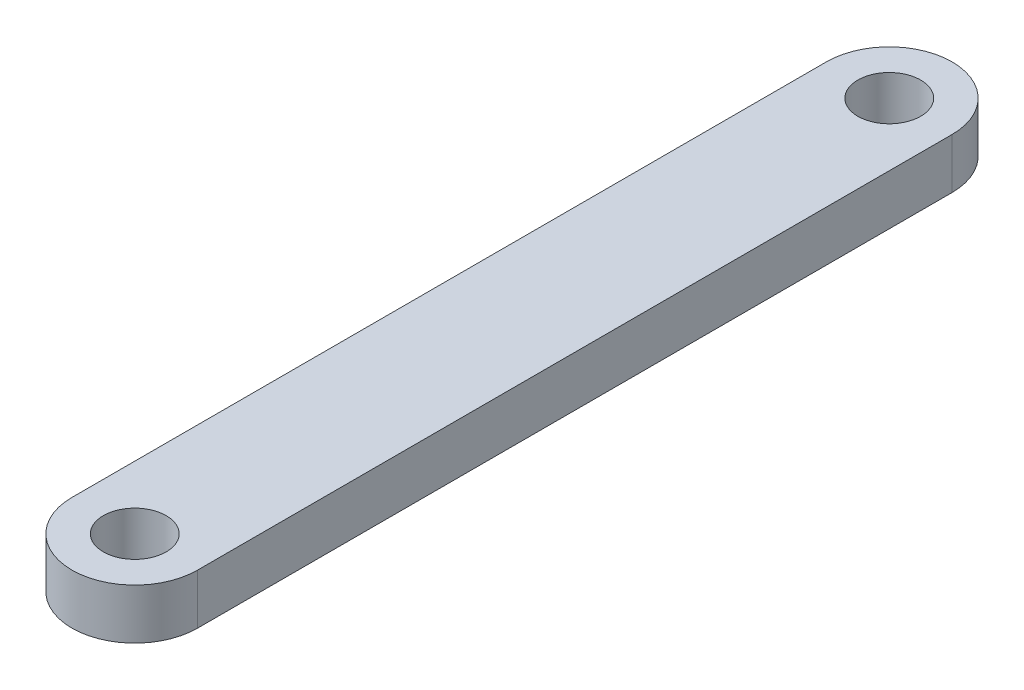
SolidWorks part; units mm, degrees
material "AISI 316 Stainless Steel Sheet (SS)"
ref_plane "Front Plane" through (0, 0, 0) normal (0, 0, 1) x (1, 0, 0)
ref_plane "Top Plane" through (0, 0, 0) normal (0, 1, 0) x (1, 0, 0)
ref_plane "Right Plane" through (0, 0, 0) normal (1, 0, 0) x (0, 0, -1)
sketch "Sketch1" plane through (0, 0, 0) normal (0, 1, 0) x (1, 0, 0)
  line L0 (-3.175, 38.1) -> (-3.175, 0)
  line L1 (3.175, 38.1) -> (3.175, 0)
  circle A0 centre (0, 0) radius 1.5875
  arc A1 (-3.175, 0) -> (3.175, 0) centre (0, 0) ccw
  circle A4 centre (0, 38.1) radius 1.5875
  arc A5 (3.175, 38.1) -> (-3.175, 38.1) centre (0, 38.1) ccw
  dimension "D2" = 6.35
  dimension "D3" = 3.175
  dimension "D1" = 38.1
  dimension "D4" = 6.35
extrude "Boss-Extrude1" add sketch "Sketch1" along normal blind 2.54
